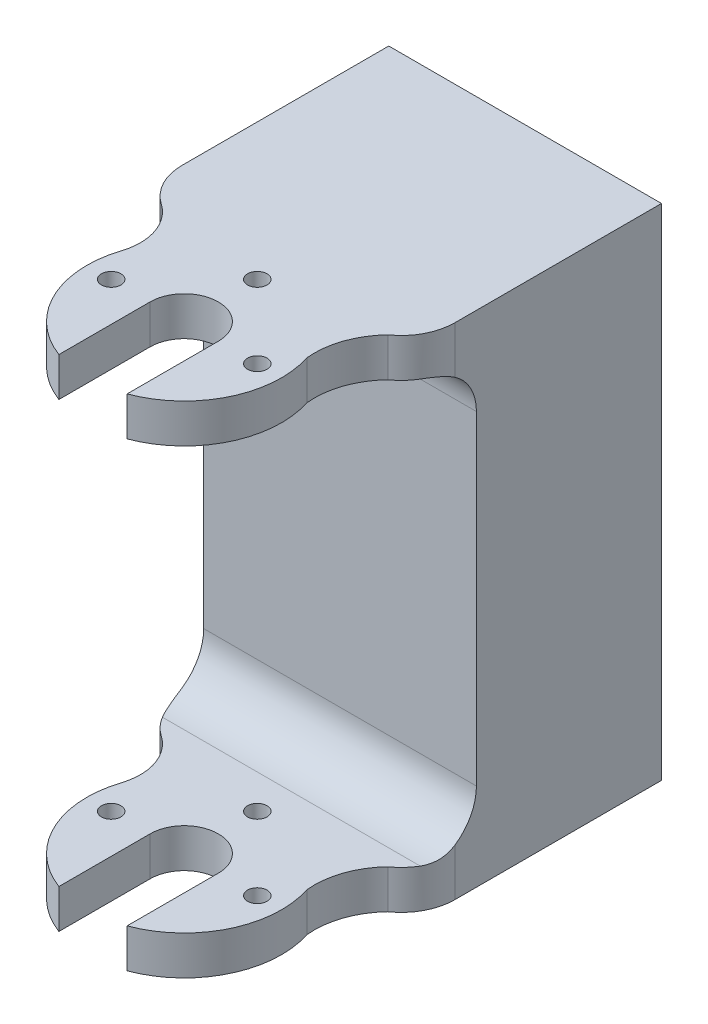
SolidWorks part; units mm, degrees
material "7075-T6 (SN)"
ref_plane "Face" through (0, 0, 0) normal (0, 0, 1) x (1, 0, 0)
ref_plane "Dessus" through (0, 0, 0) normal (0, 1, 0) x (1, 0, 0)
ref_plane "Droite" through (0, 0, 0) normal (1, 0, 0) x (0, 0, -1)
sketch "Esquisse3" plane through (0, 0, 0) normal (0, 1, 0) x (1, 0, 0)
  line L0 (-14, 0) -> (-14, -35)
  line L1 (0, 0) -> (0, -35) construction
  line L3 (14, -35) -> (14, 0)
  line L4 (-14, 0) -> (14, 0)
  line L6 (-14, 0) -> (-14, 3.841) construction
  line L7 (14, 0) -> (14, 6.0564) construction
  circle A0 centre (0, -35) radius 3.5
  arc A1 (-14, -35) -> (14, -35) centre (0, -35) ccw
  dimension "D2" = 7
  dimension "D1" = 28
  dimension "D4" = 35
extrude "Boss.-Extru.1" add sketch "Esquisse3" along normal mid plane 51.3
sketch "Esquisse5" plane through (0, 0, 0) normal (1, 0, 0) x (0, 0, -1)
  line L1 (-49, 21.65) -> (-19, 21.65)
  line L6 (-19, 21.65) -> (-19, -21.65)
  line L7 (-19, -21.65) -> (-49, -21.65)
  line L8 (-49, 25.65) -> (-49, -25.65) construction
  line L9 (-49, -21.65) -> (-49, 21.65)
  line L10 (-35, 25.65) -> (-49, 25.65) construction
  line L11 (-49, -25.65) -> (-35, -25.65) construction
  dimension "D1" = 4
  dimension "D2" = 4
  dimension "D3" = 30
extrude "Enlèv. mat.-Extru.2" cut sketch "Esquisse5" against normal through all and the other way through all
sketch "Esquisse11" plane through (0, -25.65, 0) normal (0, -1, 0) x (1, 0, 0)
  line L0 (0, 49) -> (0, 21.2035) construction
  line L1 (-14, 0) -> (-14, 35) construction
  line L3 (14, 21.2035) -> (14, 35)
  line L4 (14, 35) -> (14, 0) construction
  line L5 (-14, 21.2035) -> (14, 21.2035) construction
  line L6 (-14, 21.2035) -> (-14, 35)
  arc A0 (9.5193, 31.9368) -> (-9.5193, 31.9368) centre (0, 35) ccw
  arc A1 (-11.6274, 25.7277) -> (-14, 21.2035) centre (-8.5, 21.2035) ccw
  arc A2 (9.5193, 31.9368) -> (11.6274, 25.7277) centre (17.3235, 31.1241) ccw
  arc A3 (14, 35) -> (-14, 35) centre (0, 35) ccw construction
  arc A4 (14, 35) -> (-14, 35) centre (0, 35) ccw
  arc A5 (-9.5193, 31.9368) -> (-11.6274, 25.7277) centre (-14.7549, 30.252) cw
  arc A6 (11.6274, 25.7277) -> (14, 21.2035) centre (8.5, 21.2035) cw
  dimension "D1" = 20
  dimension "D2" = 5.5
extrude "Enlèv. mat.-Extru.6" cut sketch "Esquisse11" against normal through all
ref_plane "Plan1" through (0, 0, 45) normal (0, 0, 1) x (1, 0, 0)
sketch "Esquisse20" plane through (0, -25.65, 0) normal (0, -1, 0) x (1, 0, 0)
  line L0 (3.5, 35) -> (3.5, 46.5217)
  line L1 (3.5, 46.5217) -> (-3.5, 46.5217)
  line L2 (-3.5, 46.5217) -> (-3.5, 35)
  line L3 (-3.5, 35) -> (3.5, 35)
  circle A0 centre (0, 35) radius 3.5 construction
extrude "Enlèv. mat.-Extru.12" cut sketch "Esquisse20" against normal through all
sketch "Esquisse22" plane through (0, -25.65, 0) normal (0, -1, 0) x (1, 0, 0)
  line L0 (0, 35) -> (0, 21.0842) construction
  line L1 (0, 35) -> (15.3618, 35) construction
  circle A0 centre (0, 27.5) radius 1
  circle A1 centre (-7.5, 35) radius 1
  circle A2 centre (0, 42.5) radius 1
  circle A3 centre (7.5, 35) radius 1
  point P16 (0, 35)
  dimension "D2" = 2
  dimension "D1" = 7.5
  dimension "D3" = 4
extrude "Enlèv. mat.-Extru.14" cut sketch "Esquisse22" against normal through all
fillet "Congé2" radius 5 2 edges at (0, -21.65, 19) (0, 21.65, 19)
sketch "Esquisse23" plane through (0, 0, 0) normal (0, 0, -1) x (-1, 0, 0)
  line L1 (12, -18) -> (-12, -18)
  line L2 (12, -18) -> (12, 18)
  line L3 (12, 18) -> (-12, 18)
  line L4 (-12, -18) -> (-12, 18)
  line L7 (-14, 25.65) -> (14, 25.65) construction
  line L10 (14, 25.65) -> (14, -25.65) construction
  dimension "D1" = 36
  dimension "D2" = 7.65
  dimension "D3" = 24
  dimension "D4" = 2
extrude "Enlèv. mat.-Extru.15" cut sketch "Esquisse23" against normal blind 15
fillet "Congé3" radius 2 8 edges at (-12, 18, 7.5) (12, 18, 7.5) (12, -18, 7.5) (-12, -18, 7.5) (0, 18, 15) (12, 0, 15) (0, -18, 15) (-12, 0, 15)
